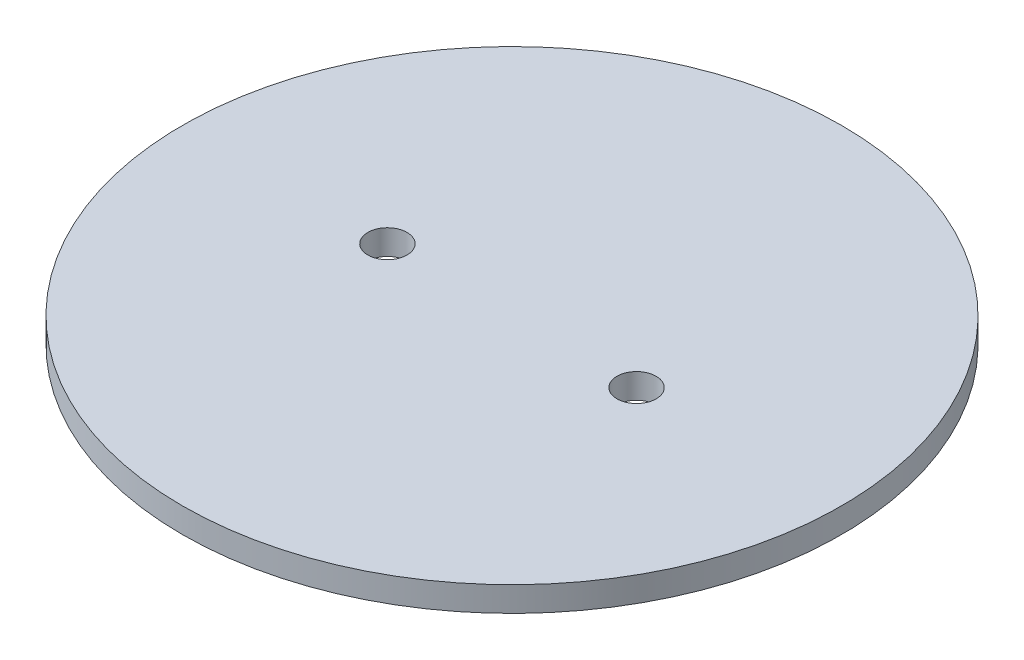
SolidWorks part; units mm, degrees
ref_plane "Front Plane" through (0, 0, 0) normal (0, 0, 1) x (1, 0, 0)
ref_plane "Top Plane" through (0, 0, 0) normal (0, 1, 0) x (1, 0, 0)
ref_plane "Right Plane" through (0, 0, 0) normal (1, 0, 0) x (0, 0, -1)
sketch "Sketch1" plane through (0, 0, 0) normal (0, 1, 0) x (1, 0, 0)
  circle A0 centre (33.6637, -33.6537) radius 33.6254
  circle A2 centre (20.9537, -33.6537) radius 2
  circle A3 centre (46.3737, -33.6537) radius 2
extrude "Boss-Extrude1" add sketch "Sketch1" along normal blind 2.54
